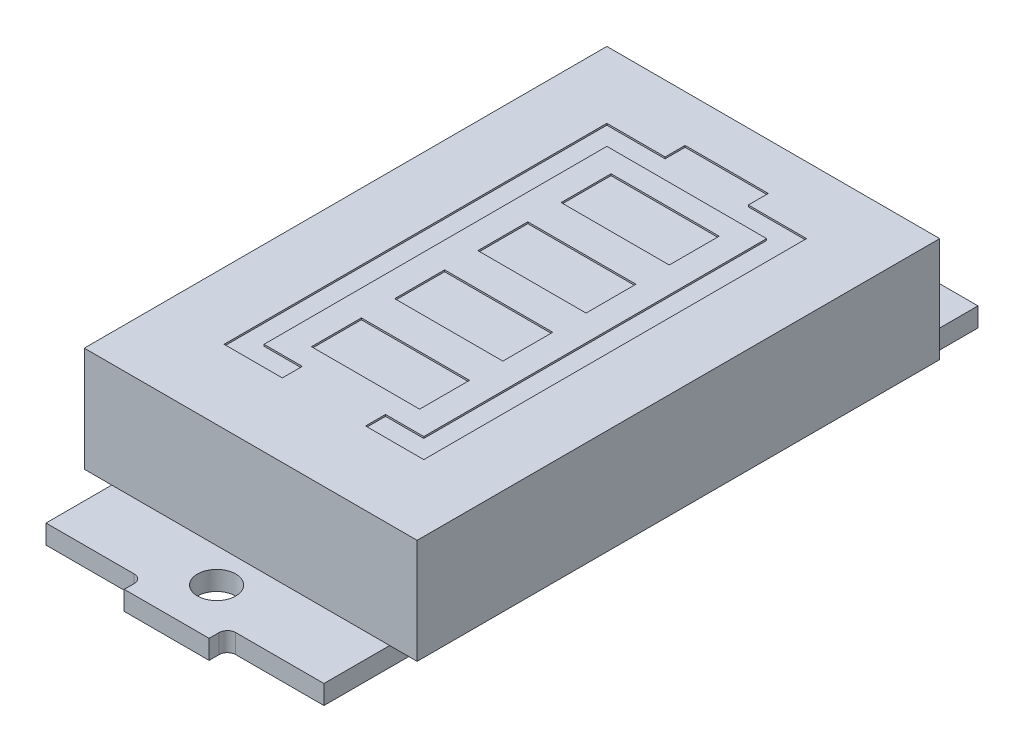
SolidWorks part; units mm, degrees
ref_plane "Plan de face" through (0, 0, 0) normal (0, 0, 1) x (1, 0, 0)
ref_plane "Plan de dessus" through (0, 0, 0) normal (0, 1, 0) x (1, 0, 0)
ref_plane "Plan de droite" through (0, 0, 0) normal (1, 0, 0) x (0, 0, -1)
sketch "Esquisse1" plane through (0, 0, 0) normal (0, 1, 0) x (1, 0, 0)
  line L0 (0, 0) -> (-8.35, 0) construction
  line L1 (0, -20.75) -> (0, 20.75) construction
  line L2 (-8.35, -19.65) -> (-8.35, 19.65)
  line L3 (-8.35, 19.65) -> (-2.55, 19.65)
  line L4 (-2.55, 19.65) -> (-2.55, 20.75)
  line L5 (-2.55, 20.75) -> (2.55, 20.75)
  line L6 (2.55, 19.65) -> (2.55, 20.75)
  line L7 (8.35, 19.65) -> (2.55, 19.65)
  line L8 (8.35, -19.65) -> (8.35, 19.65)
  line L9 (-8.35, -19.65) -> (-8.35, 19.65)
  line L10 (-8.35, 19.65) -> (-2.55, 19.65)
  line L11 (-2.55, 19.65) -> (-2.55, 20.75)
  line L12 (2.55, 19.65) -> (2.55, 20.75)
  line L13 (8.35, 19.65) -> (2.55, 19.65)
  line L14 (8.35, -19.65) -> (8.35, 19.65)
  line L15 (8.35, -19.65) -> (2.55, -19.65)
  line L16 (2.55, -19.65) -> (2.55, -20.75)
  line L17 (-2.55, -19.65) -> (-2.55, -20.75)
  line L18 (-8.35, -19.65) -> (-2.55, -19.65)
  line L19 (8.35, -19.65) -> (2.55, -19.65)
  line L20 (2.55, -19.65) -> (2.55, -20.75)
  line L21 (-2.55, -20.75) -> (2.55, -20.75)
  line L22 (-2.55, -19.65) -> (-2.55, -20.75)
  line L23 (-8.35, -19.65) -> (-2.55, -19.65)
  circle A0 centre (0, 17.75) radius 1.15
  circle A1 centre (0, -17.75) radius 1.15
  point P20 (8.35, 0)
  dimension "D6" = 2.3
  dimension "D8" = 2.3
  dimension "D1" = 20.75
  dimension "D2" = 1.1
  dimension "D3" = 2.55
  dimension "D4" = 8.35
  dimension "D5" = 3
  dimension "D7" = 3
extrude "Boss.-Extru.1" add sketch "Esquisse1" along normal blind 1.15 contours L17 L21 L16 L15 L8 L7 L6 L5 L4 L3 L2 L18 A1 A0
fillet "Congé1" radius 0.5 4 edges at (-2.55, 0.575, -19.65) (2.55, 0.575, -19.65) (-2.55, 0.575, 19.65) (2.55, 0.575, 19.65)
sketch "Esquisse2" plane through (0, 1.15, 0) normal (0, 1, 0) x (1, 0, 0)
  line L1 (-10, -15.7) -> (10, -15.7)
  line L2 (-10, -15.7) -> (-10, 15.7)
  line L3 (-10, 15.7) -> (10, 15.7)
  line L4 (10, -15.7) -> (10, 15.7)
  line L5 (-10, -15.7) -> (10, 15.7) construction
  line L6 (-10, 15.7) -> (10, -15.7) construction
  point P0 (0, 0)
  dimension "D1" = 31.4
  dimension "D2" = 20
extrude "Boss.-Extru.2" add sketch "Esquisse2" along normal blind 6.3
sketch "Esquisse4" plane through (0, 7.45, 0) normal (0, 1, 0) x (1, 0, 0)
  line L0 (0, 15.7) -> (0, -15.7) construction
  line L1 (10, 15.7) -> (-10, 15.7) construction
  line L2 (-10, -15.7) -> (10, -15.7) construction
  line L3 (-2.5, -10.1) -> (-2.5, -11.3)
  line L4 (-2.5, -11.3) -> (-6, -11.3)
  line L5 (-6, -11.3) -> (-6, 11.7)
  line L6 (-6, 11.7) -> (-2.5, 11.7)
  line L7 (-2.5, 11.7) -> (-2.5, 12.9)
  line L8 (-2.5, 12.9) -> (2.5, 12.9)
  line L9 (0, 12.9) -> (0, 10.5)
  line L10 (4.8, 10.5) -> (-4.8, 10.5)
  line L11 (-4.8, 10.5) -> (-4.8, -10.1)
  line L12 (-4.8, -10.1) -> (-2.5, -10.1)
  line L13 (3.25, 9.2) -> (-3.25, 9.2)
  line L14 (-3.25, 9.2) -> (-3.25, 6.2)
  line L15 (-3.25, 6.2) -> (3.25, 6.2)
  line L16 (0, 6.2) -> (0, 4.2)
  line L17 (3.25, 4.2) -> (-3.25, 4.2)
  line L18 (-3.25, 4.2) -> (-3.25, 1.2)
  line L19 (-3.25, 1.2) -> (3.25, 1.2)
  line L20 (3.25, -0.8) -> (-3.25, -0.8)
  line L21 (-3.25, -0.8) -> (-3.25, -3.8)
  line L22 (-3.25, -3.8) -> (3.25, -3.8)
  line L23 (3.25, -5.8) -> (-3.25, -5.8)
  line L24 (-3.25, -5.8) -> (-3.25, -8.8)
  line L25 (-3.25, -8.8) -> (3.25, -8.8)
  line L26 (-3.25, -7.3) -> (3.25, -7.3) construction
  line L27 (-3.25, -2.3) -> (3.25, -2.3) construction
  line L28 (-3.25, 2.7) -> (3.25, 2.7) construction
  line L29 (-3.25, 7.7) -> (3.25, 7.7) construction
  line L30 (3.25, -5.8) -> (3.25, -8.8)
  line L31 (3.25, -0.8) -> (3.25, -3.8)
  line L32 (3.25, 4.2) -> (3.25, 1.2)
  line L33 (3.25, 9.2) -> (3.25, 6.2)
  line L34 (4.8, -10.1) -> (2.5, -10.1)
  line L35 (4.8, 10.5) -> (4.8, -10.1)
  line L36 (2.5, 11.7) -> (2.5, 12.9)
  line L37 (6, 11.7) -> (2.5, 11.7)
  line L38 (6, -11.3) -> (6, 11.7)
  line L39 (2.5, -11.3) -> (6, -11.3)
  line L40 (2.5, -10.1) -> (2.5, -11.3)
  point P42 (0, 7.7)
  point P43 (0, 2.7)
  point P44 (0, -2.3)
  point P45 (0, -7.3)
  point P46 (0, -8.8)
  point P47 (0, -5.8)
  point P48 (0, -3.8)
  point P49 (0, -0.8)
  point P50 (0, 1.2)
  point P53 (0, 9.2)
  dimension "D1" = 23
  dimension "D2" = 1.2
  dimension "D3" = 1.2
  dimension "D4" = 1.2
  dimension "D5" = 3.5
  dimension "D6" = 6
  dimension "D7" = 1.2
  dimension "D8" = 2.5
  dimension "D9" = 3
  dimension "D10" = 3
  dimension "D11" = 3
  dimension "D12" = 3
  dimension "D13" = 5
  dimension "D14" = 5
  dimension "D15" = 5
  dimension "D16" = 2.8
  dimension "D17" = 13
  dimension "D18" = 3.25
extrude "Enlèv. mat.-Extru.1" cut sketch "Esquisse4" against normal blind 0.1 contours L34 L40 L39 L38 L37 L36 L8 L9 L10 L35 | L12 L11 L10 L9 L8 L7 L6 L5 L4 L3 | L33 L13 L14 L15 | L31 L20 L21 L22 | L30 L23 L24 L25 | L17 L18 L19 L32
